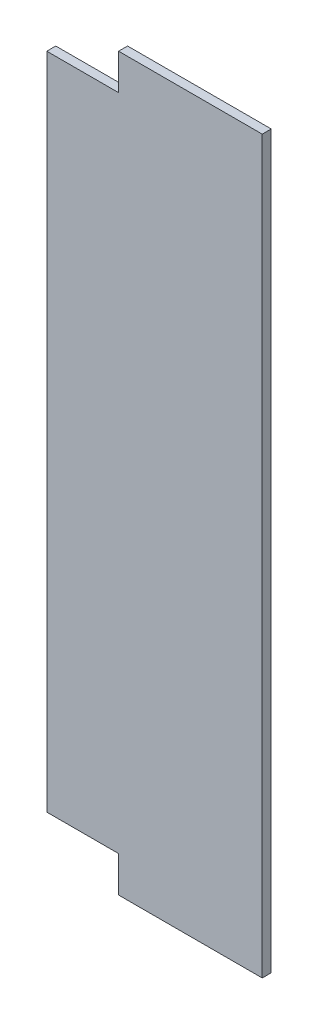
SolidWorks part; units mm, degrees
ref_plane "Front Plane" through (0, 0, 0) normal (0, 0, 1) x (1, 0, 0)
ref_plane "Top Plane" through (0, 0, 0) normal (0, 1, 0) x (1, 0, 0)
ref_plane "Right Plane" through (0, 0, 0) normal (1, 0, 0) x (0, 0, -1)
sketch "Sketch3" plane through (0, 0, 0) normal (0, 0, 1) x (1, 0, 0)
  line L0 (0, 131.7625) -> (108.2771, 131.7625) construction
  line L1 (25.4, 129.2225) -> (76.2, 129.2225)
  line L2 (0, 116.5225) -> (0, -116.5225)
  line L3 (25.4, -129.2225) -> (76.2, -129.2225)
  line L4 (76.2, 129.2225) -> (76.2, -129.2225)
  line L5 (0, 0) -> (108.2771, 0) construction
  line L6 (0, -131.7625) -> (108.2771, -131.7625) construction
  line L7 (0, 116.5225) -> (25.4, 116.5225)
  line L10 (0, -116.5225) -> (25.4, -116.5225)
  line L11 (25.4, -129.2225) -> (25.4, -116.5225)
  line L12 (25.4, 129.2225) -> (25.4, 116.5225)
  point P4 (0, 0)
  dimension "D1" = 263.525
  dimension "D2" = 76.2
  dimension "D3" = 25.4
  dimension "D4" = 12.7
  dimension "D5" = 258.445
extrude "Boss-Extrude1" add sketch "Sketch3" along normal mid plane 3.175
